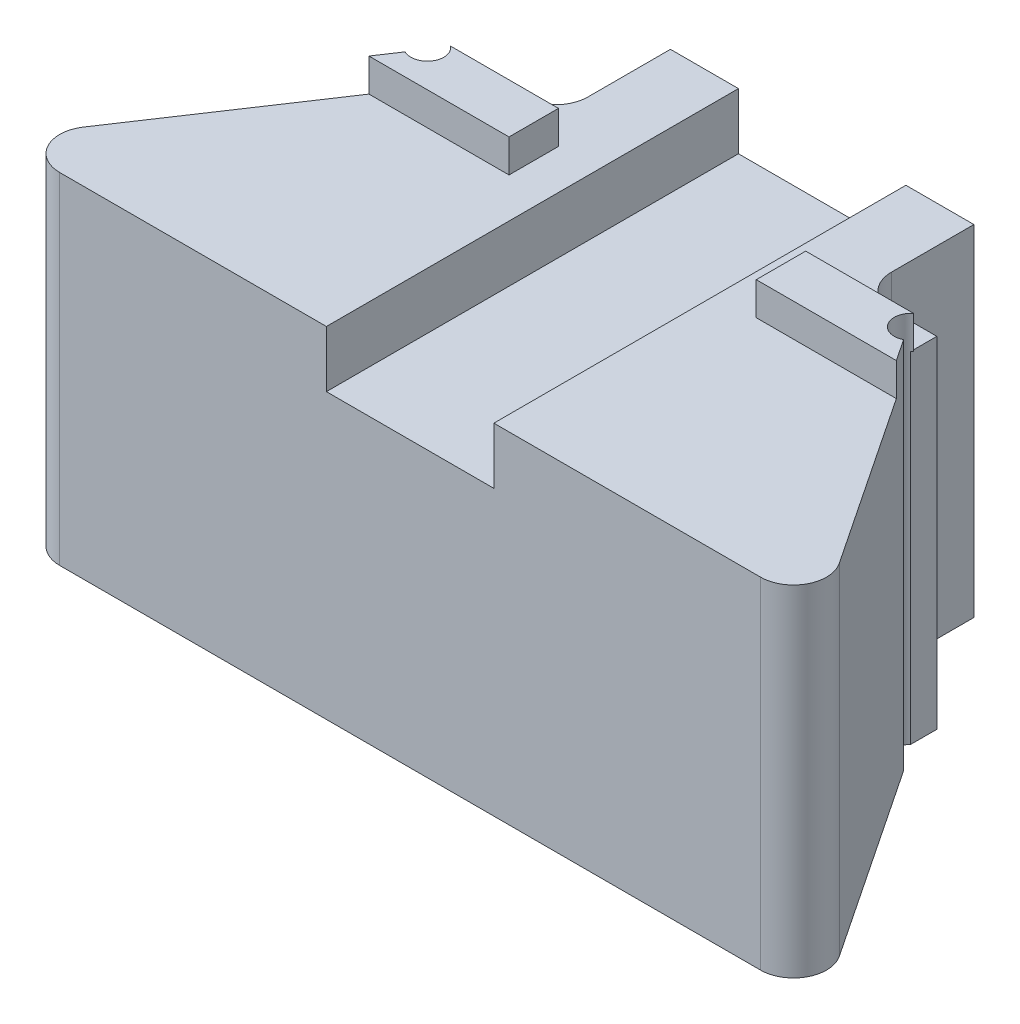
SolidWorks part; units mm, degrees
material "99.5% Aluminum Oxide"
ref_plane "Front Plane" through (0, 0, 0) normal (0, 0, 1) x (1, 0, 0)
ref_plane "Top Plane" through (0, 0, 0) normal (0, 1, 0) x (1, 0, 0)
ref_plane "Right Plane" through (0, 0, 0) normal (1, 0, 0) x (0, 0, -1)
sketch "Sketch1" plane through (0, 0, 0) normal (0, 1, 0) x (1, 0, 0)
  line L1 (-15, -12.5) -> (15, -12.5)
  line L2 (-15, -12.5) -> (-15, 12.5) construction
  line L3 (-15, 12.5) -> (15, 12.5) construction
  line L4 (15, -12.5) -> (15, 12.5) construction
  line L5 (-15, -12.5) -> (15, 12.5) construction
  line L6 (-15, 12.5) -> (15, -12.5) construction
  line L8 (-9.2062, 12.5) -> (9.2062, 12.5)
  line L11 (0, 11.2271) -> (0, -49988.7729) construction
  line L12 (-14.2062, 2.5) -> (-15, 2.5)
  line L13 (14.2063, 2.5) -> (15, 2.5)
  line L14 (-15, 2.5) -> (-25, -12.5)
  line L15 (-25, -12.5) -> (-15, -12.5)
  line L16 (15, 2.5) -> (25, -12.5)
  line L17 (25, -12.5) -> (15, -12.5)
  line L18 (-14.2062, 2.5) -> (-14.2062, 5.5)
  line L19 (-14.2062, 5.5) -> (-9.2062, 5.5)
  line L20 (-9.2062, 5.5) -> (-9.2062, 12.5)
  line L21 (14.2063, 2.5) -> (14.2062, 5.5)
  line L22 (14.2062, 5.5) -> (9.2062, 5.5)
  line L23 (9.2062, 5.5) -> (9.2062, 12.5)
  point P0 (0, 0)
  point P14 (0, 12.5)
  dimension "D1" = 25
  dimension "D2" = 30
  dimension "D3" = 10
  dimension "D4" = 15
  dimension "D5" = 0.7937
  dimension "D6" = 3
  dimension "D7" = 5
extrude "Boss-Extrude1" add sketch "Sketch1" along normal mid plane 20.65
sketch "Sketch4" plane through (0, 10.325, 0) normal (0, 1, 0) x (1, 0, 0)
  line L0 (-14.2062, 2.5) -> (-15, 2.5) construction
  line L2 (14.2062, 2.5) -> (13.9562, 2.5)
  line L3 (0, 0) -> (0, 50000) construction
  line L4 (-14.2062, 5.5) -> (-13.9562, 5.5)
  line L5 (-14.2062, 5.5) -> (-14.2062, 2.5)
  line L6 (-14.2062, 2.5) -> (-13.9562, 2.5)
  line L7 (-13.9562, 5.5) -> (-13.9562, 2.5)
  line L12 (13.9562, 5.5) -> (13.9562, 2.5)
  line L13 (14.2062, 5.5) -> (13.9562, 5.5)
  line L14 (14.2062, 5.5) -> (14.2062, 2.5)
  dimension "D1" = 0.25
extrude "Cut-Extrude4" cut sketch "Sketch4" against normal through all both and the other way through all
sketch "Sketch5" plane through (0, 10.325, 0) normal (0, 1, 0) x (1, 0, 0)
  line L0 (-13.9562, 2.5) -> (-14.6634, 3.2071) construction
  line L1 (-13.9562, 2.5) -> (-13.9562, 5.5) construction
  line L2 (-13.9562, 2.5) -> (-15, 2.5) construction
  line L3 (0, 0) -> (0, 50000) construction
  circle A0 centre (-14.6634, 3.2071) radius 1
  circle A1 centre (14.6634, 3.2071) radius 1
  point P2 (-13.9562, 3.9142)
  point P3 (-15.3705, 2.5)
  point P4 (-13.9562, 2.5)
  dimension "D1" = 2
  dimension "D2" = 45
extrude "Cut-Extrude5" cut sketch "Sketch5" against normal through all both and the other way through all
fillet "Fillet5" radius 2 4 edges at (25, 0, 12.5) (-25, 0, 12.5) (9.2062, 0, -5.5) (-9.2062, 0, -5.5)
sketch "Sketch6" plane through (0, 10.325, 0) normal (0, 1, 0) x (1, 0, 0)
  line L1 (-14.054, 4) -> (-7.5, 4)
  line L2 (-7.5, 4) -> (-7.5, 1)
  line L3 (-7.5, 1) -> (-16, 1)
  line L5 (-15.1213, 2.3181) -> (-16, 1)
  line L6 (-15.1213, 2.3181) -> (-22.9271, -9.3906) construction
  line L8 (22.9271, -9.3906) -> (15.1213, 2.3181) construction
  line L9 (16, 1) -> (15.1213, 2.3181)
  line L10 (14.054, 4) -> (7.5, 4)
  line L11 (7.5, 4) -> (7.5, 1)
  line L12 (7.5, 1) -> (16, 1)
  line L13 (9.2062, 12.5) -> (-9.2062, 12.5) construction
  arc A0 (-15.1213, 2.3181) -> (-13.9562, 3.9142) centre (-14.6634, 3.2071) ccw construction
  arc A1 (13.9562, 3.9142) -> (15.1213, 2.3181) centre (14.6634, 3.2071) ccw construction
  arc A2 (-14.054, 4) -> (-15.1213, 2.3181) centre (-14.6634, 3.2071) cw
  arc A3 (14.054, 4) -> (15.1213, 2.3181) centre (14.6634, 3.2071) ccw
  dimension "D1" = 8.5
  dimension "D2" = 15
  dimension "D3" = 3
extrude "Boss-Extrude2" add sketch "Sketch6" along normal blind 2
sketch "Sketch7" plane through (0, 0, 12.5) normal (0, 0, 1) x (1, 0, 0)
  line L0 (-21.263, 10.325) -> (21.263, 10.325) construction
  line L1 (-5.08, 10.325) -> (5.08, 10.325)
  line L2 (-5.08, 10.325) -> (-5.08, 6.9)
  line L3 (-5.08, 6.9) -> (5.08, 6.9)
  line L4 (5.08, 10.325) -> (5.08, 6.9)
  point P6 (0, 10.325)
  point P7 (0, 10.325)
  dimension "D1" = 10.16
  dimension "D2" = 3.425
extrude "Cut-Extrude6" cut sketch "Sketch7" against normal through all
equation "\"panel_width\"= 5.5in"
equation "\"finger_joint_width\"= 30mm"
